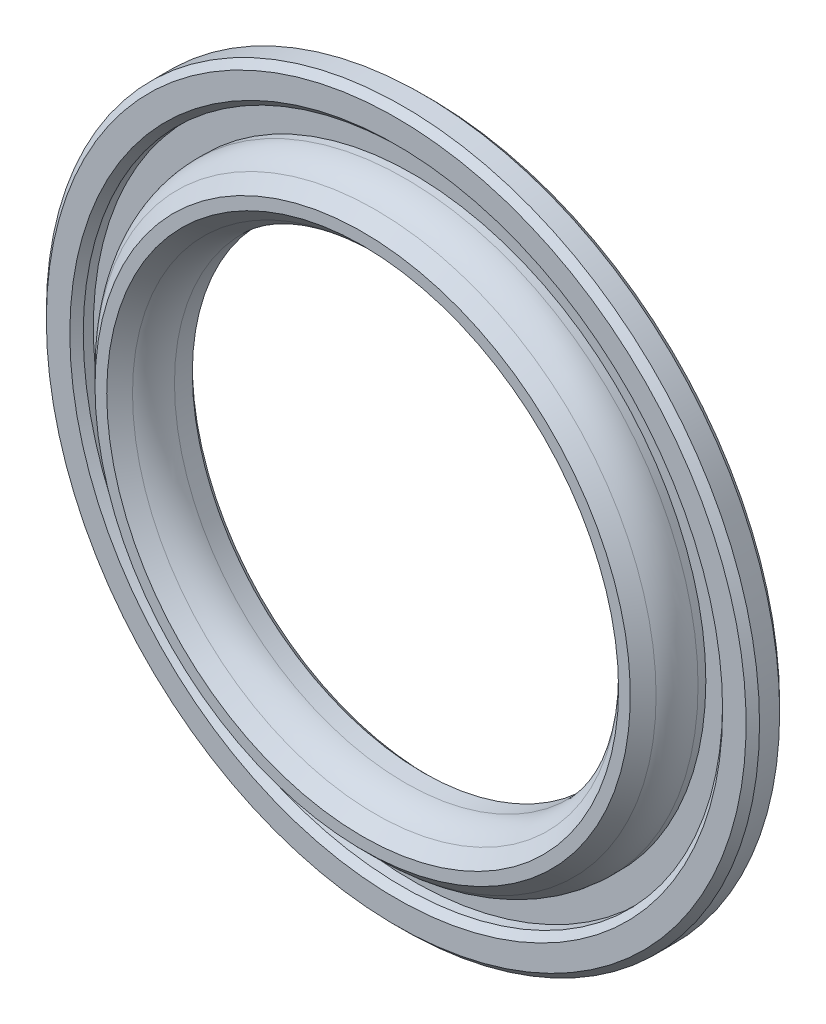
SolidWorks part; units mm, degrees
ref_plane "Ebene vorne" through (0, 0, 0) normal (0, 0, 1) x (1, 0, 0)
ref_plane "Ebene oben" through (0, 0, 0) normal (0, 1, 0) x (1, 0, 0)
ref_plane "Ebene rechts" through (0, 0, 0) normal (1, 0, 0) x (0, 0, -1)
sketch "Skizze3" plane through (0, 0, 0) normal (1, 0, 0) x (0, 0, -1)
  line L0 (-28.0822, 0) -> (28.4247, 0) construction
  line L1 (0, 27.5) -> (0, 34.9)
  line L2 (0, 34.9) -> (6, 34.9)
  line L3 (6, 34.9) -> (6, 38.1)
  line L4 (6, 38.1) -> (4, 38.1)
  line L5 (4, 38.1) -> (4, 42.5)
  line L6 (4, 42.5) -> (8, 42.5)
  line L8 (8, 27.5) -> (0, 27.5)
  line L9 (8, 42.5) -> (8, 27.5)
  dimension "D1" = 55
  dimension "D2" = 69.8
  dimension "D3" = 76.2
  dimension "D4" = 2
  dimension "D5" = 8
  dimension "D6" = 4
  dimension "D7" = 85
revolve "Rotation1" add sketch "Skizze3" angle 360 about L0
chamfer "Fase1" distance 0.8 4 edges at (38.1, 0, -4) (27.5, 0, -8) (42.5, 0, -8) (42.5, 0, -4)
chamfer "Fase2" distance 3 angle 45 2 edges at (27.5, 0, 0) (34.9, 0, 0)
fillet "Verrundung1" radius 5 2 edges at (-27.5, 0, -3) (-34.9, 0, -3)
